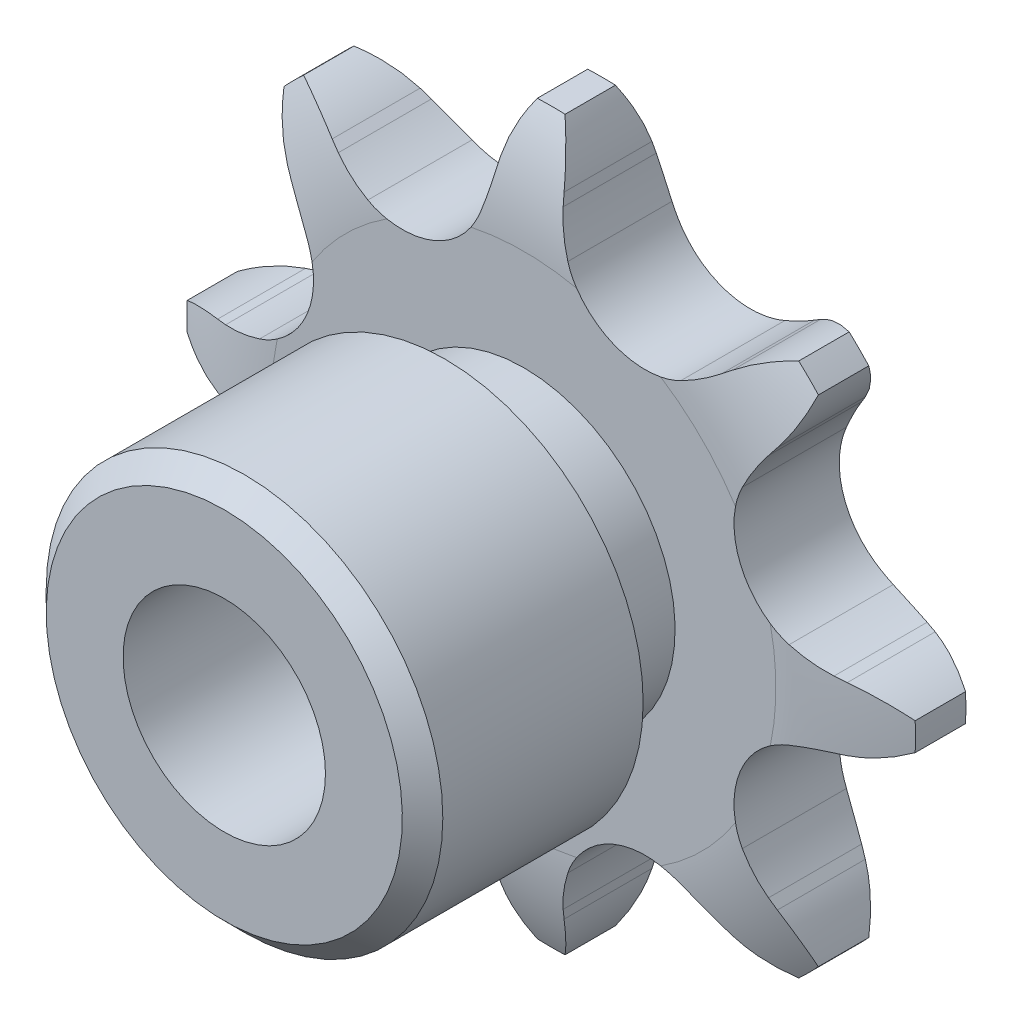
SolidWorks part; units mm, degrees
ref_plane "Front Plane" through (0, 0, 0) normal (0, 0, 1) x (1, 0, 0)
ref_plane "Top Plane" through (0, 0, 0) normal (0, 1, 0) x (1, 0, 0)
ref_plane "Right Plane" through (0, 0, 0) normal (1, 0, 0) x (0, 0, -1)
sketch "Sketch0" plane through (0, 0, 0) normal (0, 0, 1) x (1, 0, 0)
  line L0 (3, -7.2426) -> (0, 0) construction
  line L1 (0, 0) -> (7.2426, -3) construction
  line L2 (0, 0) -> (-3, -7.2426) construction
  line L3 (3, -7.2426) -> (7.2426, -3) construction
  line L4 (3, -7.2426) -> (-3, -7.2426) construction
  line L5 (4.9471, -6.053) -> (4.7324, -5.897)
  line L6 (3, -7.2426) -> (0, -8.4853) construction
  line L7 (0.782, -7.7783) -> (0.8235, -7.5161)
  line L8 (0, -7.2426) -> (0, -9.0426) construction
  line L9 (3.8656, -5.3864) -> (1.6476, -10.1428) construction
  line L10 (0, 0) -> (0, -7.2426) construction
  line L11 (4.7324, -5.897) -> (1.6476, -10.1428) construction
  line L12 (0, -9.0426) -> (0, -9.4708) construction
  line L13 (6.9598, -3.2828) -> (4.9471, -6.053) construction
  circle A0 centre (0, 0) radius 9.0426 construction
  circle A1 centre (0, 0) radius 7.8394 construction
  arc A2 (-3.7569, -10.4654) -> (10.0567, -4.7436) centre (0, 0) ccw
  circle A3 centre (0, 0) radius 9.4708 construction
  circle A4 centre (3, -7.2426) radius 2 construction
  arc A7 (3.8656, -5.3864) -> (1.0754, -6.5421) centre (3, -7.2426) ccw
  circle A8 centre (3, -7.2426) radius 2.0481 construction
  arc A9 (4.9471, -6.053) -> (10.0567, -4.7436) centre (6.9598, -3.2828) ccw
  arc A10 (4.7324, -5.897) -> (3.8656, -5.3864) centre (1.6476, -10.1428) ccw
  arc A11 (0.782, -7.7783) -> (-3.7569, -10.4654) centre (-2.6, -7.2426) cw
  arc A12 (0.8235, -7.5161) -> (1.0754, -6.5421) centre (6.007, -8.3371) cw
  dimension "D1" = 2.0481
  dimension "R" = 2.0481
sketch "Sketch1" plane through (0, 0, 0) normal (1, 0, 0) x (0, 0, -1)
  line L0 (1.3, 0) -> (-1.3, 0)
  line L1 (-1.3, 0) -> (-1.3, 6.2302)
  line L2 (-1.3, 7.8394) -> (0, 7.8394) construction
  line L3 (-0.6, 9.0426) -> (0.6, 9.0426)
  line L5 (1.3, 6.2302) -> (1.3, 0)
  line L7 (0, 9.0426) -> (0, 0) construction
  line L8 (-1.3, 6.2302) -> (1.3, 6.2302) construction
  line L9 (0, 9.0426) -> (0, -9.0426) construction
  line L10 (-1.3, 6.2302) -> (-1.3, 9.0426) construction
  line L11 (-1.3, 9.0426) -> (-0.6, 9.0426) construction
  line L12 (0.6, 9.0426) -> (1.3, 9.0426) construction
  line L13 (1.3, 9.0426) -> (1.3, 6.2302) construction
  line L14 (0, 0) -> (-6.4008, 0) construction
  line L15 (-1.3, 7.8394) -> (-1.3, 3.7394) construction
  line L22 (1.3, 0) -> (-8.7, 0) construction
  line L24 (-1.3, 0) -> (-1.3, 3.7394) construction
  arc A0 (-0.6, 9.0426) -> (-1.3, 6.2302) centre (4.7, 6.2302) ccw
  arc A1 (0.6, 9.0426) -> (1.3, 6.2302) centre (-4.7, 6.2302) cw
  dimension "R" = 6
revolve "Revolve1" add sketch "Sketch1" angle 360 mid plane about L0
extrude "Cut-Extrude1" cut sketch "Sketch0" against normal through all and the other way through all
pattern_circular "CirPattern1" count 8 over 360 about axis through (0, 0, 0) along (0, 0, 1) of "Cut-Extrude1"
sketch "Sketch2" plane through (0, 0, 0) normal (0, 0, 1) x (1, 0, 0)
  circle A0 centre (0, 0) radius 2.5 construction
  circle A1 centre (0, 0) radius 4.9
  circle A2 centre (0, 0) radius 9 construction
  dimension "Bore" = 5
  dimension "Hub Dia." = 9.8
  dimension "OD" = 18
extrude "Boss-Extrude1" add sketch "Sketch2" along normal up to vertex (8.7 mm away) from surface at 1.3 starting at face at (0, 0, 1.3)
sketch "Sketch3" plane through (0, 0, 0) normal (0, 0, 1) x (1, 0, 0)
  circle A0 centre (0, 0) radius 2.5 construction
  circle A1 centre (0, 0) radius 2.5
extrude "Cut-Extrude2" cut sketch "Sketch3" along normal through all and the other way through all
sketch "Sketch4" plane through (0, 0, 0) normal (1, 0, 0) x (0, 0, -1)
  line L0 (-8.7, 4.9) -> (-8.7, 4.4)
  line L1 (-1.3, 9.0426) -> (-3.25, 9.0426)
  line L2 (-1.3, 9.0426) -> (-1.3, 3.7394)
  line L3 (-1.3, 3.7394) -> (-3.25, 3.7394)
  line L4 (-3.25, 9.0426) -> (-3.25, 3.7394)
  line L9 (-8.7, 4.4) -> (-8.2, 4.9)
  line L10 (-8.2, 4.9) -> (-8.7, 4.9)
  dimension "C" = 0.5
  dimension "D3" = 1.95
revolve "Cut-Revolve1" cut sketch "Sketch4" angle 360 mid plane about L22
sketch "Sketch5" plane through (0, 0, 0) normal (0, 0, 1) x (1, 0, 0)
  circle A0 centre (0, 0) radius 9 construction
  circle A1 centre (0, 0) radius 9
extrude "Cut-Extrude3" cut sketch "Sketch5" against normal through all and the other way through all flip side to cut
equation "\"360/N@Sketch0\" = 360/\"Teeth@CirPattern1\""
equation "\"Ds@Sketch0\" = 1.005 * \"Dr@Sketch0\" + ( 0.003 * 25.4 ) "
equation "\"R@Sketch0\" = 1/2 * \"Ds@Sketch0\""
equation "\"A@Sketch0\" = 35 +  ( 60 / \"Teeth@CirPattern1\" ) "
equation "\"B@Sketch0\" = 18 -  ( 56 / \"Teeth@CirPattern1\" )"
equation "\"ac@Sketch0\" = 0.8 * \"Dr@Sketch0\""
equation "\"ab@Sketch0\" = 1.4 * \"Dr@Sketch0\""
equation "\"J@Sketch0\" = 0.3 * \"Pitch@Sketch0\""
equation "\"D3@Sketch4\" = \"t@Sketch1\" * 3 / 4"
